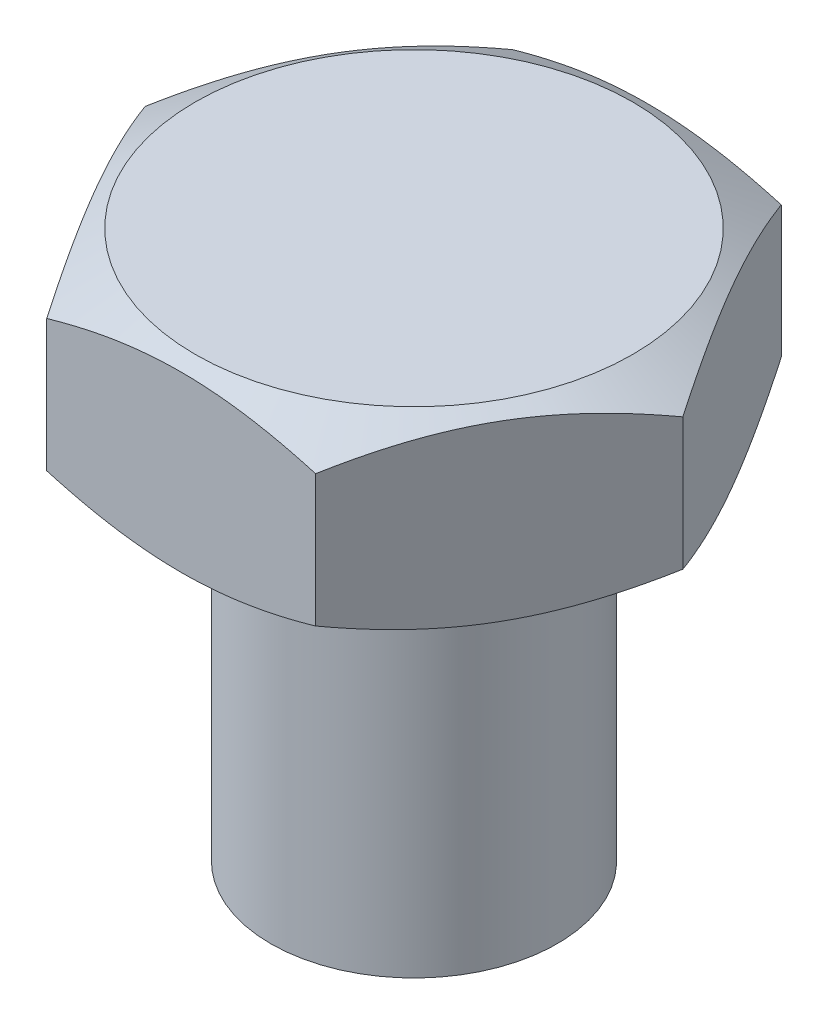
SolidWorks part; units mm, degrees
material "合金钢"
ref_plane "前视基准面" through (0, 0, 0) normal (0, 0, 1) x (1, 0, 0)
ref_plane "上视基准面" through (0, 0, 0) normal (0, 1, 0) x (1, 0, 0)
ref_plane "右视基准面" through (0, 0, 0) normal (1, 0, 0) x (0, 0, -1)
sketch "Sketch1" plane through (0, 0, 0) normal (0, 1, 0) x (1, 0, 0)
  line L1 (7.5056, 0) -> (3.7528, 6.5)
  line L2 (3.7528, 6.5) -> (-3.7528, 6.5)
  line L3 (-3.7528, 6.5) -> (-7.5056, 0)
  line L4 (-7.5056, 0) -> (-3.7528, -6.5)
  line L5 (-3.7528, -6.5) -> (3.7528, -6.5)
  line L6 (3.7528, -6.5) -> (7.5056, 0)
  circle A0 centre (0, 0) radius 6.5 construction
  dimension "S" = 13
extrude "Extrude1" add sketch "Sketch1" against normal blind 5.3
sketch "Sketch2" plane through (0, -5.3, 0) normal (0, -1, 0) x (1, 0, 0)
  circle A0 centre (0, 0) radius 4
  dimension "D" = 8
extrude "Extrude2" add sketch "Sketch2" along normal blind 10
sketch "Sketch3" plane through (0, 0, 0) normal (0, 0, 1) x (1, 0, 0)
  line L0 (6.1056, 0) -> (7.5056, 0)
  line L1 (3.7528, 0) -> (7.5056, 0) construction
  line L2 (7.5056, 0) -> (7.5056, -0.8083)
  line L3 (7.5056, -5.3) -> (7.5056, 0) construction
  line L4 (7.5056, -0.8083) -> (6.1056, 0)
  line L5 (7.5056, -5.3) -> (7.5056, -4.4917)
  line L6 (7.5056, -4.4917) -> (6.1056, -5.3)
  line L7 (3.7528, -5.3) -> (7.5056, -5.3) construction
  line L8 (6.1056, -5.3) -> (7.5056, -5.3)
  line L9 (0, -1000) -> (0, 49000) construction
  dimension "D1" = 1.4
  dimension "D2" = 30
revolve "Cut-Revolve1" cut sketch "Sketch3" angle 360 about L9
other "冻结***"
